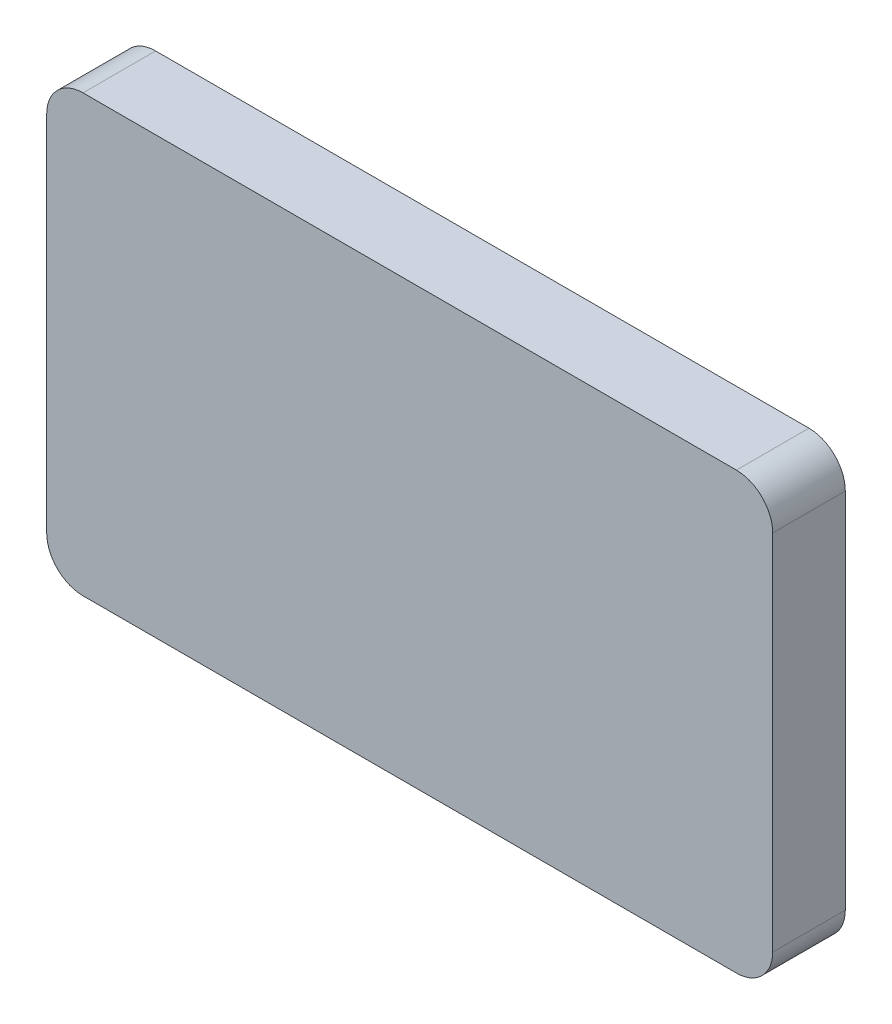
SolidWorks part; units mm, degrees
ref_plane "Front Plane" through (0, 0, 0) normal (0, 0, 1) x (1, 0, 0)
ref_plane "Top Plane" through (0, 0, 0) normal (0, 1, 0) x (1, 0, 0)
ref_plane "Right Plane" through (0, 0, 0) normal (1, 0, 0) x (0, 0, -1)
sketch "Sketch1" plane through (0, 0, 0) normal (0, 0, 1) x (1, 0, 0)
  line L1 (-63.5, -38.1) -> (63.5, -38.1)
  line L2 (-63.5, -38.1) -> (-63.5, 38.1)
  line L3 (-63.5, 38.1) -> (63.5, 38.1)
  line L4 (63.5, -38.1) -> (63.5, 38.1)
  line L5 (-63.5, -38.1) -> (63.5, 38.1) construction
  line L6 (-63.5, 38.1) -> (63.5, -38.1) construction
  point P0 (0, 0)
  dimension "D1" = 127
  dimension "D2" = 76.2
extrude "Boss-Extrude2" add sketch "Sketch1" along normal blind 12.7
fillet "Fillet2" radius 6.35 4 edges at (-63.5, -38.1, 6.35) (63.5, -38.1, 6.35) (63.5, 38.1, 6.35) (-63.5, 38.1, 6.35)
sketch "Sketch4" plane through (0, 0, 12.7) normal (0, 0, 1) x (1, 0, 0)
  line L0 (8.7616, -38.1) -> (57.15, -38.1)
  line L1 (-3.9384, -38.1) -> (8.7616, -38.1) construction
  line L2 (8.7616, 38.1) -> (-3.9384, 38.1) construction
  line L3 (-3.9384, 38.1) -> (-57.15, 38.1)
  line L4 (-63.5, 31.75) -> (-63.5, -31.75)
  line L5 (-57.15, -38.1) -> (57.15, -38.1)
  line L6 (63.5, -31.75) -> (63.5, 31.75)
  line L7 (57.15, 38.1) -> (-57.15, 38.1)
  line L8 (-63.5, 31.75) -> (-63.5, -31.75)
  line L9 (-57.15, -38.1) -> (-3.9384, -38.1)
  line L10 (63.5, -31.75) -> (63.5, 31.75)
  line L11 (57.15, 38.1) -> (8.7616, 38.1)
  line L12 (-57.15, -38.1) -> (57.15, -38.1) construction
  arc A4 (-63.5, -31.75) -> (-57.15, -38.1) centre (-57.15, -31.75) ccw
  arc A5 (57.15, -38.1) -> (63.5, -31.75) centre (57.15, -31.75) ccw
  arc A6 (63.5, 31.75) -> (57.15, 38.1) centre (57.15, 31.75) ccw
  arc A7 (-57.15, 38.1) -> (-63.5, 31.75) centre (-57.15, 31.75) ccw
  arc A8 (-63.5, -31.75) -> (-57.15, -38.1) centre (-57.15, -31.75) ccw
  arc A9 (57.15, -38.1) -> (63.5, -31.75) centre (57.15, -31.75) ccw
  arc A10 (63.5, 31.75) -> (57.15, 38.1) centre (57.15, 31.75) ccw
  arc A11 (-57.15, 38.1) -> (-63.5, 31.75) centre (-57.15, 31.75) ccw
  dimension "D2" = 12.7
  dimension "D3" = 12.7
  dimension "D1" = 0
